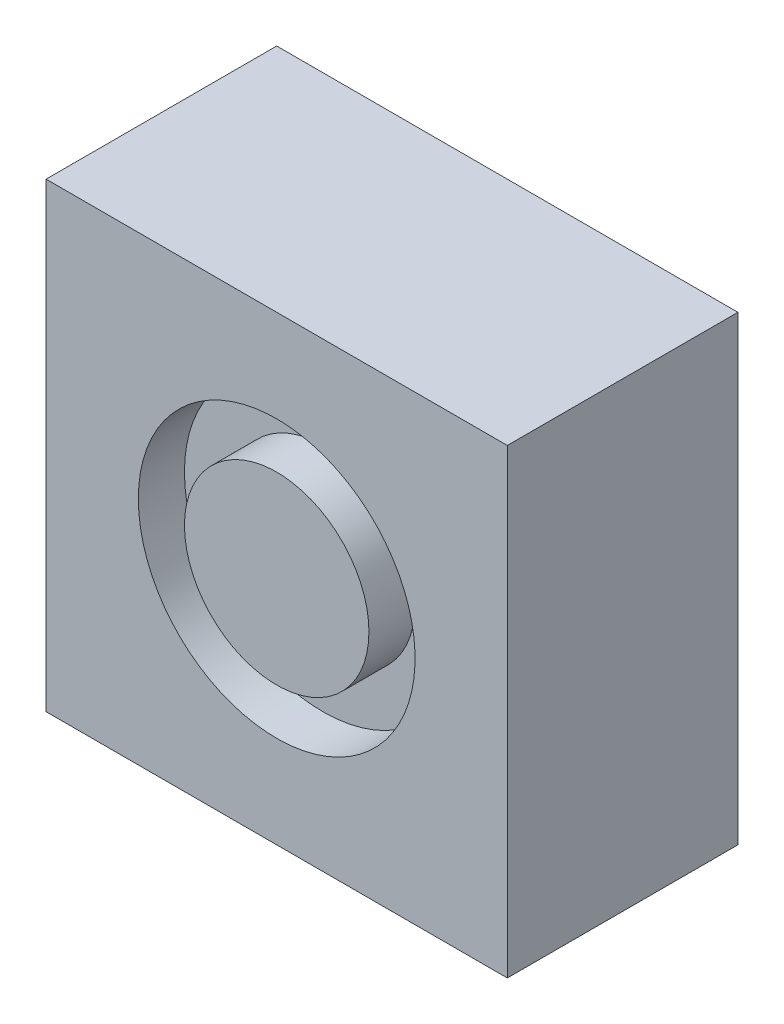
SolidWorks part; units mm, degrees
ref_plane "Ebene vorne" through (0, 0, 0) normal (0, 0, 1) x (1, 0, 0)
ref_plane "Ebene oben" through (0, 0, 0) normal (0, 1, 0) x (1, 0, 0)
ref_plane "Ebene rechts" through (0, 0, 0) normal (1, 0, 0) x (0, 0, -1)
sketch "Skizze1" plane through (0, 0, 0) normal (0, 0, 1) x (1, 0, 0)
  line L1 (50, -50) -> (-50, -50)
  line L2 (50, -50) -> (50, 50)
  line L3 (50, 50) -> (-50, 50)
  line L4 (-50, -50) -> (-50, 50)
  line L5 (50, -50) -> (-50, 50) construction
  line L6 (50, 50) -> (-50, -50) construction
  point P0 (0, 0)
  dimension "D1" = 100
  dimension "D2" = 100
extrude "Aufsatz-Linear austragen1" add sketch "Skizze1" along normal blind 50
sketch "Skizze2" plane through (0, 0, 50) normal (0, 0, 1) x (1, 0, 0)
  line L0 (-32.5238, 0) -> (32.7771, 0) construction
  circle A0 centre (0, 0) radius 25
  point P5 (-25, 0)
  dimension "D1" = 50
sketch "Skizze5" plane through (0, 0, 0) normal (0, 1, 0) x (1, 0, 0)
  line L1 (-20, -40) -> (-30, -40)
  line L2 (-20, -40) -> (-20, -60)
  line L3 (-20, -60) -> (-30, -60)
  line L4 (-30, -40) -> (-30, -60)
  line L5 (-20, -40) -> (-30, -60) construction
  line L6 (-20, -60) -> (-30, -40) construction
  point P0 (-25, -50)
  dimension "D1" = 10
  dimension "D2" = 20
sweep "Schnitt-Austragung1" cut profiles "Skizze5" path "Skizze2"
